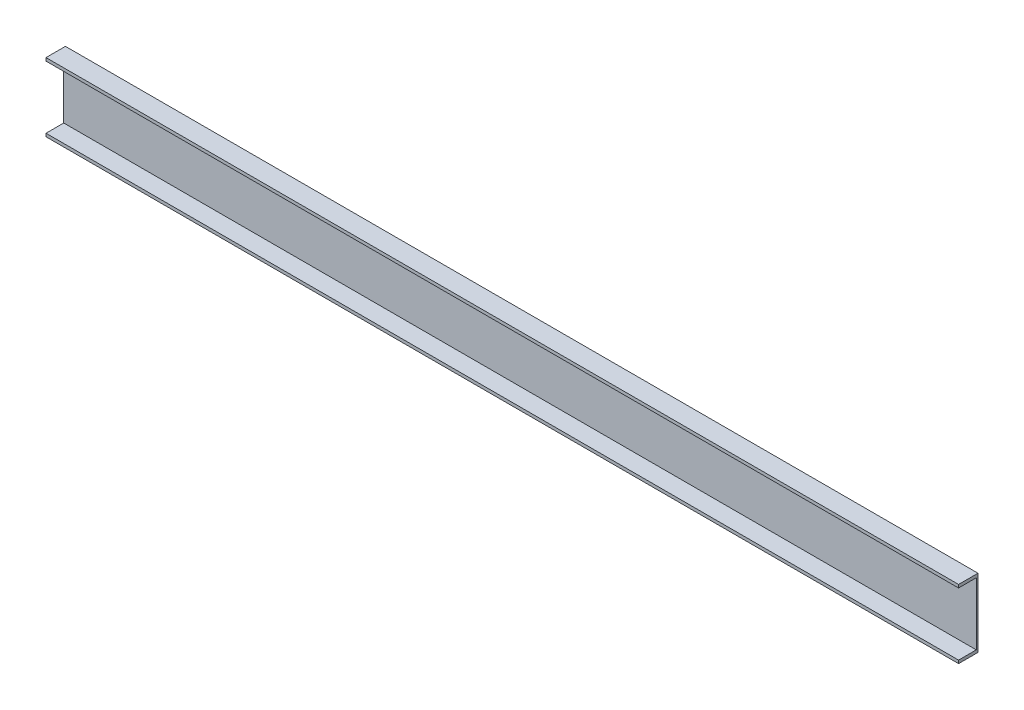
SolidWorks part; units mm, degrees
ref_plane "前视" through (0, 0, 0) normal (0, 0, 1) x (1, 0, 0)
ref_plane "上视" through (0, 0, 0) normal (0, 1, 0) x (1, 0, 0)
ref_plane "右视" through (0, 0, 0) normal (1, 0, 0) x (0, 0, -1)
sketch "草图1" plane through (0, 0, 0) normal (0, 0, 1) x (1, 0, 0)
  line L0 (-253.2778, 0) -> (2143.7198, 0) construction
  line L1 (0, 293.7967) -> (0, -293.7967) construction
  line L2 (1484.3386, 80) -> (1995, 80) construction
  line L3 (-1995, 150) -> (1995, 150)
  line L4 (-1995, 150) -> (-1995, -150)
  line L5 (-1995, -150) -> (1995, -150)
  line L6 (1995, 150) -> (1995, -150)
  line L7 (1940, 137.9179) -> (1940, -34.3032) construction
  line L8 (1860, 137.9179) -> (1860, -34.3032) construction
  line L9 (1780, -27.7215) -> (1780, 137.9179) construction
  line L10 (1700, 137.9179) -> (1700, -27.7215) construction
  line L11 (24.2318, 80) -> (382.2761, 80) construction
  line L12 (60, 137.9179) -> (60, -34.3032) construction
  line L13 (140, -34.3032) -> (140, 137.9179) construction
  dimension "D1" = 300
  dimension "D2" = 3990
  dimension "D3" = 80
  dimension "D4" = 55
  dimension "D5" = 80
  dimension "D6" = 80
  dimension "D7" = 80
  dimension "D9" = 60
  dimension "D10" = 80
extrude "基体-拉伸" add sketch "草图1" along normal blind 7.5
sketch "草图2" plane through (0, 0, 7.5) normal (0, 0, 1) x (1, 0, 0)
  line L0 (1995, -150) -> (1995, 150) construction
  line L1 (-1995, 150) -> (1995, 150)
  line L2 (-1995, 150) -> (-1995, 136.5)
  line L3 (-1995, 136.5) -> (1995, 136.5)
  line L4 (1995, 150) -> (1995, 136.5)
  line L5 (-335.9089, 0) -> (412.8346, 0) construction
  line L6 (1995, -150) -> (1995, -136.5)
  line L7 (-1995, -136.5) -> (1995, -136.5)
  line L8 (-1995, -150) -> (-1995, -136.5)
  line L9 (-1995, -150) -> (1995, -150)
  dimension "D1" = 13.5
extrude "凸台-拉伸1" add sketch "草图2" along normal blind 77.5
